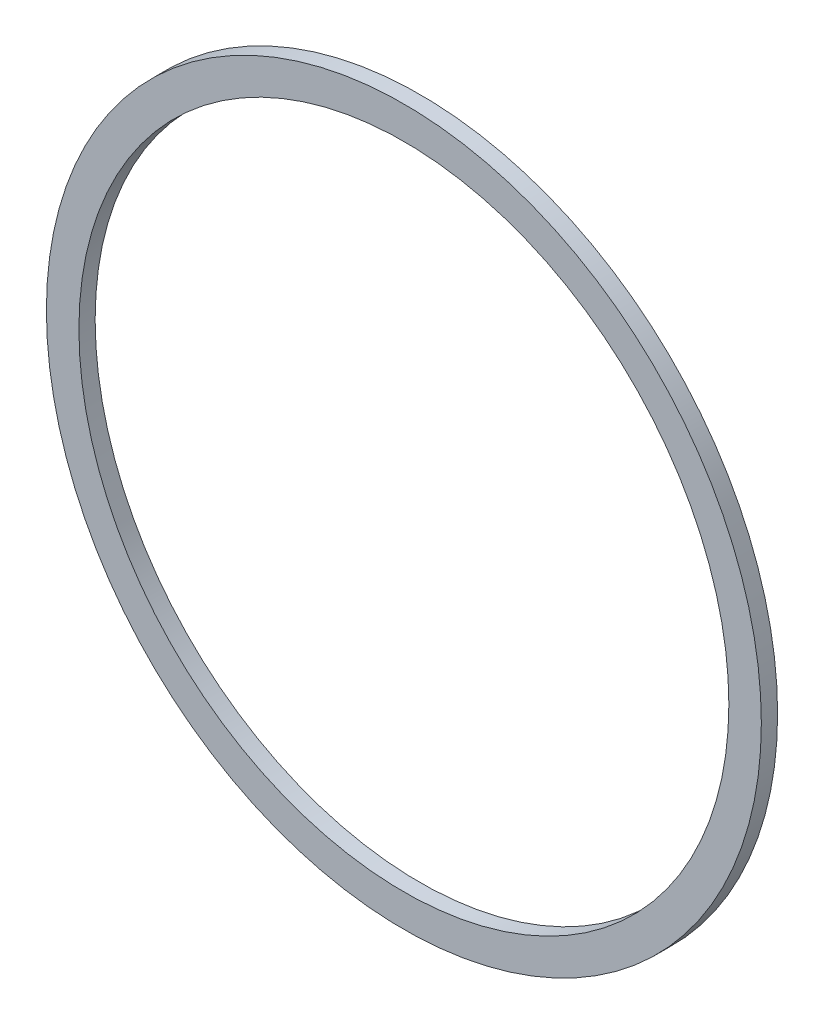
SolidWorks part; units mm, degrees
ref_plane "Plane1" through (0, 0, 0) normal (0, 0, 1) x (1, 0, 0)
ref_plane "Plane2" through (0, 0, 0) normal (0, 1, 0) x (1, 0, 0)
ref_plane "Plane3" through (0, 0, 0) normal (1, 0, 0) x (0, 0, -1)
other "Configuration Table"
sketch "Sketch1" plane through (0, 0, 0) normal (0, 0, 1) x (1, 0, 0)
  circle A0 centre (0, 0) radius 508
  circle A1 centre (0, 0) radius 558.8
  dimension "D1" = 1016
  dimension "D2" = 1117.6
extrude "Base-Extrude" add sketch "Sketch1" against normal blind 25.4
